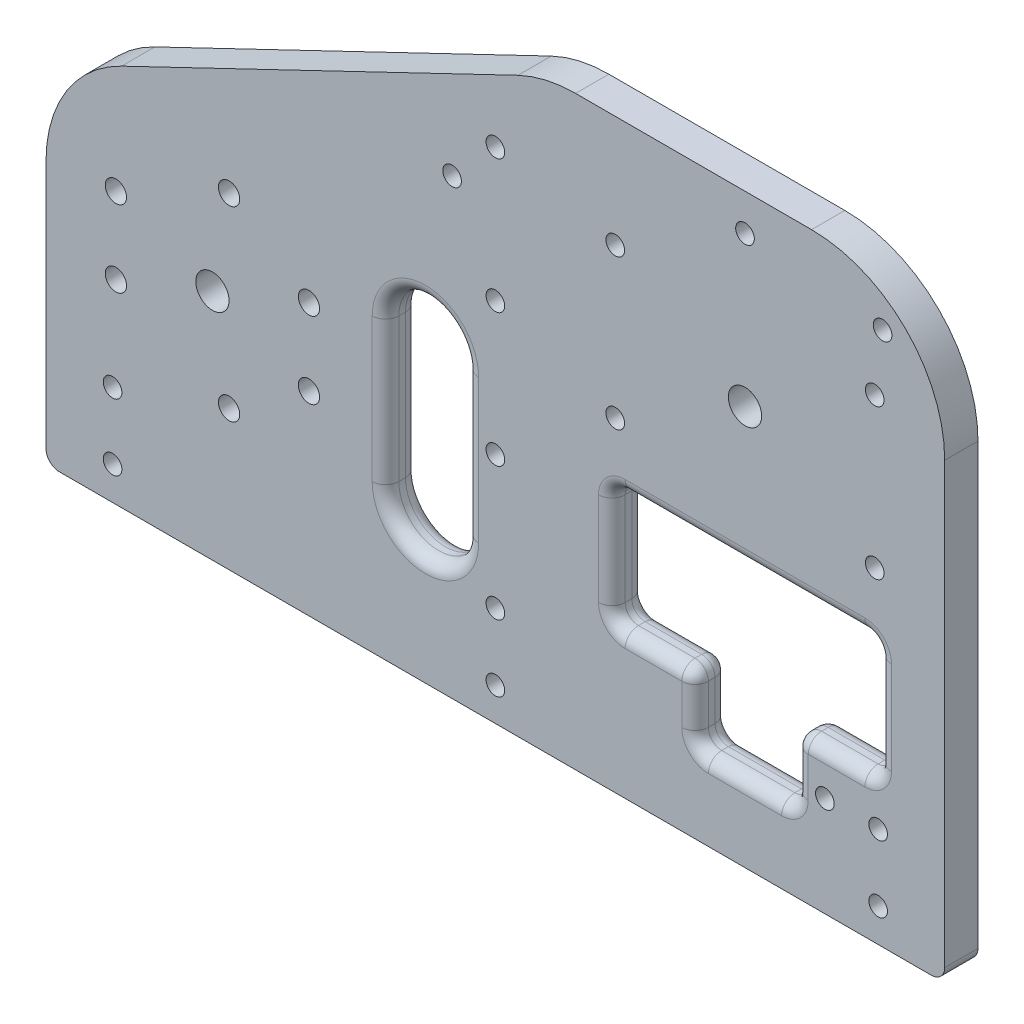
SolidWorks part; units mm, degrees
ref_plane "Front Plane" through (0, 0, 0) normal (0, 0, 1) x (1, 0, 0)
ref_plane "Top Plane" through (0, 0, 0) normal (0, 1, 0) x (1, 0, 0)
ref_plane "Right Plane" through (0, 0, 0) normal (1, 0, 0) x (0, 0, -1)
sketch "Sketch1" plane through (0, 0, 0) normal (0, 0, 1) x (1, 0, 0)
  line L1 (0, 0) -> (-135, 0)
  line L2 (0, 0) -> (0, 135)
  line L3 (0, 135) -> (-135, 135)
  line L4 (-135, 0) -> (-135, 135)
  circle A0 centre (-110, 35) radius 2.5
  circle A1 centre (-110, 35) radius 25 construction
  circle A2 centre (-30, 60) radius 25 construction
  circle A3 centre (-30, 60) radius 2.5
  dimension "D3" = 50
  dimension "D4" = 5
  dimension "D5" = 60
  dimension "D1" = 135
  dimension "D2" = 135
  dimension "D6" = 80
  dimension "D7" = 35
extrude "Boss-Extrude1" add sketch "Sketch1" along normal blind 5
sketch "Sketch2" plane through (0, 0, 0) normal (0, 0, -1) x (-1, 0, 0)
  arc A0 (30, 81.475) -> (30, 83.525) centre (30, 82.5) ccw construction
  arc A1 (10.5144, 72.275) -> (10.5144, 70.225) centre (10.5144, 71.25) ccw construction
  arc A2 (10.5144, 49.775) -> (10.5144, 47.725) centre (10.5144, 48.75) ccw construction
  arc A3 (49.4856, 47.725) -> (49.4856, 49.775) centre (49.4856, 48.75) ccw construction
  arc A4 (49.4856, 70.225) -> (49.4856, 72.275) centre (49.4856, 71.25) ccw construction
  arc A5 (30, 81.475) -> (30, 83.525) centre (30, 82.5) ccw construction
  arc A6 (10.5144, 72.275) -> (10.5144, 70.225) centre (10.5144, 71.25) ccw construction
  arc A7 (10.5144, 49.775) -> (10.5144, 47.725) centre (10.5144, 48.75) ccw construction
  arc A8 (49.4856, 47.725) -> (49.4856, 49.775) centre (49.4856, 48.75) ccw construction
  arc A9 (49.4856, 70.225) -> (49.4856, 72.275) centre (49.4856, 71.25) ccw construction
  circle A10 centre (95.5, 29.25) radius 1.4 construction
  circle A11 centre (95.5, 40.75) radius 1.4 construction
  circle A12 centre (107.5, 21) radius 1.4 construction
  circle A13 centre (124.5, 29.25) radius 1.4 construction
  circle A14 centre (124.5, 40.75) radius 1.4 construction
  circle A15 centre (107.5, 49) radius 1.4 construction
  circle A16 centre (95.5, 29.25) radius 1.4 construction
  circle A17 centre (95.5, 40.75) radius 1.4 construction
  circle A18 centre (107.5, 21) radius 1.4 construction
  circle A19 centre (124.5, 29.25) radius 1.4 construction
  circle A20 centre (124.5, 40.75) radius 1.4 construction
  circle A21 centre (107.5, 49) radius 1.4 construction
  circle A22 centre (30, 82.5) radius 1.4
  circle A23 centre (49.4856, 71.25) radius 1.4
  circle A24 centre (49.4856, 48.75) radius 1.4
  circle A25 centre (10.5144, 48.75) radius 1.4
  circle A26 centre (10.5144, 71.25) radius 1.4
  circle A27 centre (95.5, 40.75) radius 1.6
  circle A28 centre (107.5, 49) radius 1.6
  circle A29 centre (124.5, 40.75) radius 1.6
  circle A30 centre (124.5, 29.25) radius 1.6
  circle A31 centre (107.5, 21) radius 1.6
  circle A32 centre (95.5, 29.25) radius 1.6
  dimension "D1" = 2.8
  dimension "D2" = 3.2
extrude "Cut-Extrude1" cut sketch "Sketch2" against normal through all
sketch "Sketch4" plane through (0, 0, 5) normal (0, 0, 1) x (1, 0, 0)
  line L4 (-135, 0) -> (0, 0) construction
  line L8 (-12, 0) -> (0, 0)
  line L9 (0, 0) -> (0, 88)
  line L10 (0, 0) -> (0, 135) construction
  line L11 (0, 88) -> (-60, 88)
  line L12 (-60, 88) -> (-135, 52)
  line L13 (-135, 135) -> (-135, 0) construction
  line L14 (-135, 52) -> (-135, 0)
  line L15 (-135, 0) -> (-85, 0)
  line L16 (-85, 0) -> (-12, 0)
  line L17 (-291.4738, 198.9501) -> (189.038, 198.9501)
  line L18 (-291.4738, 198.9501) -> (-291.4738, -152.3389)
  line L19 (-291.4738, -152.3389) -> (189.038, -152.3389)
  line L20 (189.038, 198.9501) -> (189.038, -152.3389)
  arc A1 (-23.754, 85.2386) -> (-48.3848, 78.3848) centre (-30, 60) ccw construction
  dimension "D2" = 12
  dimension "D3" = 50
  dimension "D4" = 60
  dimension "D5" = 28
  dimension "D7" = 52
extrude "Cut-Extrude2" cut sketch "Sketch4" against normal through all
sketch "Sketch7" plane through (0, 0, 5) normal (0, 0, 1) x (1, 0, 0)
  line L0 (-24, 37.5) -> (-16, 37.5) construction
  line L1 (-10, 21.5) -> (-22.5, 21.5)
  line L2 (-10, 21.5) -> (-10, 39.5)
  line L3 (-10, 39.5) -> (-50, 39.5)
  line L4 (-50, 21.5) -> (-50, 39.5)
  line L5 (0, 0) -> (0, 88) construction
  line L6 (-37.5, 21.5) -> (-37.5, 11.5)
  line L7 (-37.5, 11.5) -> (-22.5, 11.5)
  line L8 (-22.5, 11.5) -> (-22.5, 21.5)
  line L9 (-30, 39.5) -> (-30, 11.5) construction
  line L10 (-37.5, 21.5) -> (-50, 21.5)
  dimension "D1" = 2
  dimension "D2" = 40
  dimension "D3" = 18
  dimension "D4" = 10
  dimension "D5" = 15
  dimension "D6" = 10
extrude "Cut-Extrude4" cut sketch "Sketch7" against normal through all
fillet "Fillet1" radius 20 3 edges at (-60, 88, 2.5) (-135, 52, 2.5) (0, 88, 2.5)
sketch "Sketch5" plane through (0, 0, 5) normal (0, 0, 1) x (1, 0, 0)
  line L0 (-135, 5) -> (0, 5) construction
  line L1 (-135, 15) -> (0, 15) construction
  line L2 (-135, 0) -> (0, 0) construction
  line L3 (-135, 39.4153) -> (-135, 0) construction
  line L4 (0, 0) -> (0, 68) construction
  line L5 (-125, 15) -> (-125, 5) construction
  line L6 (-67.5, 15) -> (-67.5, 5) construction
  line L7 (-67.5, 5) -> (-67.5, 0) construction
  line L8 (-135, 0) -> (0, 0) construction
  line L9 (-67.5, 0) -> (-67.5, 10.6834) construction
  circle A0 centre (-125, 15) radius 1.4
  circle A1 centre (-125, 5) radius 1.4
  circle A2 centre (-67.5, 5) radius 1.4
  circle A3 centre (-67.5, 15) radius 1.4
  circle A4 centre (-10, 5) radius 1.4
  circle A5 centre (-10, 15) radius 1.4
  circle A6 centre (-67.5, 35) radius 1.4
  circle A7 centre (-67.5, 55) radius 1.4
  circle A8 centre (-67.5, 75) radius 1.4
  circle A9 centre (-9.333, 80.2719) radius 1.4
  dimension "D3" = 2.8
  dimension "D6" = 2.8
  dimension "D1" = 5
  dimension "D2" = 10
  dimension "D4" = 10
  dimension "D5" = 4
extrude "Cut-Extrude3" cut sketch "Sketch5" against normal through all
sketch "Sketch8" plane through (0, 0, 5) normal (0, 0, 1) x (1, 0, 0)
  line L0 (-78, 43.7695) -> (-78, 22.2305) construction
  line L1 (-72, 43.7695) -> (-72, 22.2305)
  line L2 (-84, 43.7695) -> (-84, 22.2305)
  line L3 (-135, 0) -> (0, 0) construction
  arc A0 (-72, 43.7695) -> (-84, 43.7695) centre (-78, 43.7695) ccw
  arc A1 (-84, 22.2305) -> (-72, 22.2305) centre (-78, 22.2305) ccw
  circle A2 centre (-110, 35) radius 2.5 construction
  point P2 (-78, 33)
  dimension "D1" = 33
  dimension "D2" = 32
  dimension "D3" = 12
extrude "Cut-Extrude5" cut sketch "Sketch8" against normal through all
fillet "Fillet2" radius 2 34 edges at (0, 0, 2.5) (-135, 0, 2.5) (-16.25, 21.5, 0) (-16.25, 21.5, 5) (-10, 30.5, 0) (-50, 30.5, 0) (-10, 30.5, 5) (-50, 30.5, 5) (-30, 39.5, 0) (-30, 39.5, 5) (-10, 39.5, 2.5) (-10, 21.5, 2.5) (-50, 39.5, 2.5) (-72, 33, 0) (-78, 16.2305, 0) (-84, 33, 0) (-78, 49.7695, 5) (-72, 33, 5) (-78, 16.2305, 5) (-78, 49.7695, 0) (-84, 33, 5) (-30, 11.5, 0) (-30, 11.5, 5) (-22.5, 11.5, 2.5) (-22.5, 16.5, 0) (-22.5, 21.5, 2.5) (-22.5, 16.5, 5) (-37.5, 16.5, 0) (-37.5, 11.5, 2.5) (-37.5, 16.5, 5) (-50, 21.5, 2.5) (-43.75, 21.5, 0) (-37.5, 21.5, 2.5) (-43.75, 21.5, 5)
sketch "Sketch9" plane through (0, 0, 5) normal (0, 0, 1) x (1, 0, 0)
  line L0 (-133, 0) -> (-2, 0) construction
  circle A0 centre (-18, 15) radius 1.4
  circle A1 centre (-74, 68) radius 1.4
  dimension "D1" = 12
  dimension "D2" = 2.8
  dimension "D4" = 44
  dimension "D3" = 15
  dimension "D5" = 8
extrude "Cut-Extrude6" cut sketch "Sketch9" against normal through all
